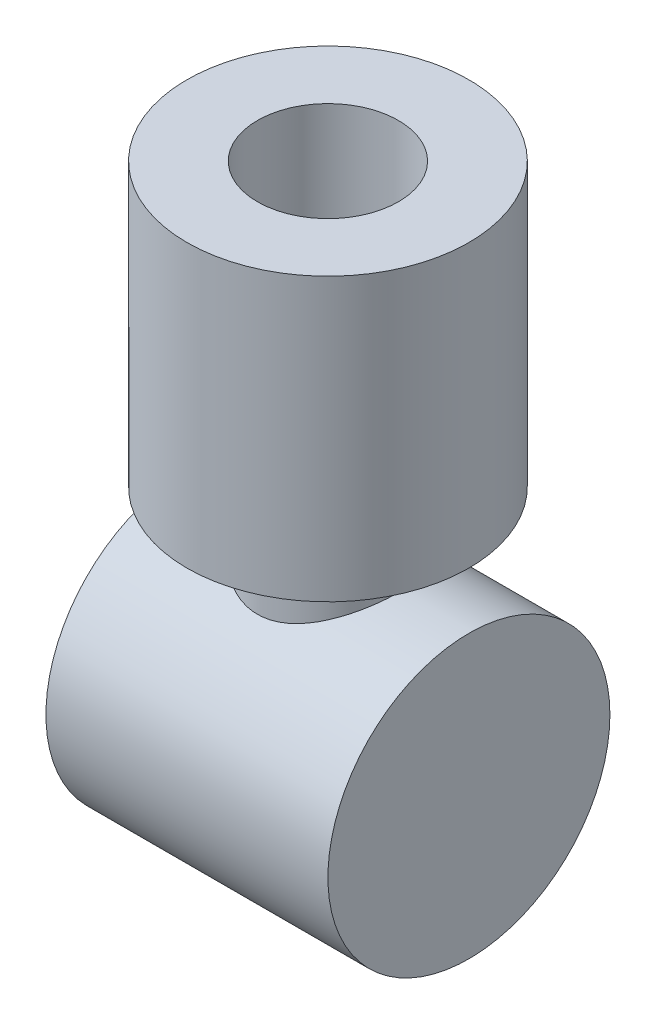
SolidWorks part; units mm, degrees
ref_plane "Front" through (0, 0, 0) normal (0, 0, 1) x (1, 0, 0)
ref_plane "Top" through (0, 0, 0) normal (0, 1, 0) x (1, 0, 0)
ref_plane "Right" through (0, 0, 0) normal (1, 0, 0) x (0, 0, -1)
sketch "Croquis1" plane through (0, 0, 0) normal (1, 0, 0) x (0, 0, -1)
  circle A0 centre (0, 0) radius 50
  dimension "D1" = 100
extrude "Saliente-Extruir1" add sketch "Croquis1" along normal mid plane 100
sketch "Croquis2" plane through (0, 0, 0) normal (0, 1, 0) x (1, 0, 0)
  circle A0 centre (0, 0) radius 25
  dimension "D1" = 50
extrude "Saliente-Extruir2" add sketch "Croquis2" along normal blind 70
sketch "Croquis4" plane through (0, 70, 0) normal (0, 1, 0) x (1, 0, 0)
  circle A0 centre (0, 0) radius 50
  dimension "D1" = 100
extrude "Saliente-Extruir3" add sketch "Croquis4" along normal blind 100
sketch "Croquis5" plane through (0, 170, 0) normal (0, 1, 0) x (1, 0, 0)
  circle A0 centre (0, 0) radius 25
  dimension "D1" = 50
extrude "Cortar-Extruir1" cut sketch "Croquis5" against normal blind 50
